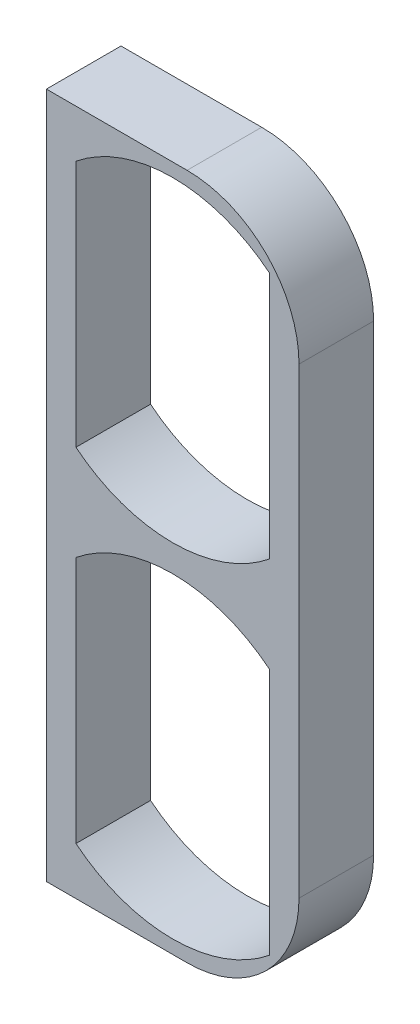
SolidWorks part; units mm, degrees
ref_plane "Front Plane" through (0, 0, 0) normal (0, 0, 1) x (1, 0, 0)
ref_plane "Top Plane" through (0, 0, 0) normal (0, 1, 0) x (1, 0, 0)
ref_plane "Right Plane" through (0, 0, 0) normal (1, 0, 0) x (0, 0, -1)
sketch "Sketch1" plane through (0, 0, 0) normal (0, 0, 1) x (1, 0, 0)
  line L1 (-23.7871, -29.21) -> (23.7871, -29.21)
  line L2 (-23.7871, -29.21) -> (-23.7871, 29.21)
  line L3 (-23.7871, 29.21) -> (23.7871, 29.21)
  line L4 (23.7871, -29.21) -> (23.7871, 29.21)
  line L5 (-23.7871, -29.21) -> (23.7871, 29.21) construction
  line L6 (-23.7871, 29.21) -> (23.7871, -29.21) construction
  point P0 (0, 0)
  dimension "D1" = 58.42
  dimension "D2" = 47.5742
extrude "Boss-Extrude1" add sketch "Sketch1" along normal blind 12.7
sketch "Sketch3" plane through (0, 0, 12.7) normal (0, 0, 1) x (1, 0, 0)
  line L0 (0, -26.924) -> (0, 26.924)
  line L1 (-16.0782, 0) -> (16.0782, 0)
  line L2 (-16.4716, 21.0877) -> (-16.4716, -21.0877)
  line L3 (16.4716, 21.0877) -> (16.4716, -21.0877)
  arc A0 (0, 26.924) -> (16.4716, 21.0877) centre (0, 0.762) cw
  arc A1 (0, 26.924) -> (-16.4716, 21.0877) centre (0, 0.762) ccw
  arc A2 (0, -26.924) -> (-16.4716, -21.0877) centre (0, -0.762) cw
  arc A3 (0, -26.924) -> (16.4716, -21.0877) centre (0, -0.762) ccw
  point P4 (0, 0)
  point P6 (0, 0)
  point P9 (0, 0)
  point P12 (-16.0782, 0)
  point P15 (16.0782, 0)
  dimension "D5" = 26.162
  dimension "D1" = 53.848
  dimension "D2" = 32.1564
  dimension "D3" = 42.1755
  dimension "D4" = 42.1755
  dimension "D6" = 26.162
extrude "Cut-Extrude1" cut sketch "Sketch3" against normal up to next contours L0 A1 L2 L1 | A0 L0 L1 L3 | A2 L0 L1 L2 | L0 A3 L3 L1
mirror "Mirror1" about plane through (-23.7871, 29.21, 12.7) normal (0, -1, 0) of bodies 103
sketch "Sketch4" plane through (23.7871, 0, 0) normal (1, 0, 0) x (0, 0, -1)
  line L1 (-12.7, -29.21) -> (0, -29.21)
  line L2 (-12.7, -29.21) -> (-12.7, 87.63)
  line L3 (-12.7, 87.63) -> (0, 87.63)
  line L4 (0, -29.21) -> (0, 87.63)
extrude "Cut-Extrude2" cut sketch "Sketch4" against normal blind 2.286
sketch "Sketch5" plane through (-23.7871, 0, 0) normal (-1, 0, 0) x (0, 0, 1)
  line L1 (12.7, 87.63) -> (0, 87.63)
  line L2 (12.7, 87.63) -> (12.7, -29.21)
  line L3 (12.7, -29.21) -> (0, -29.21)
  line L4 (0, 87.63) -> (0, -29.21)
extrude "Cut-Extrude3" cut sketch "Sketch5" against normal blind 2.286
fillet "Fillet1" radius 19.05 2 edges at (21.5011, -29.21, 6.35) (21.5011, 87.63, 6.35)
